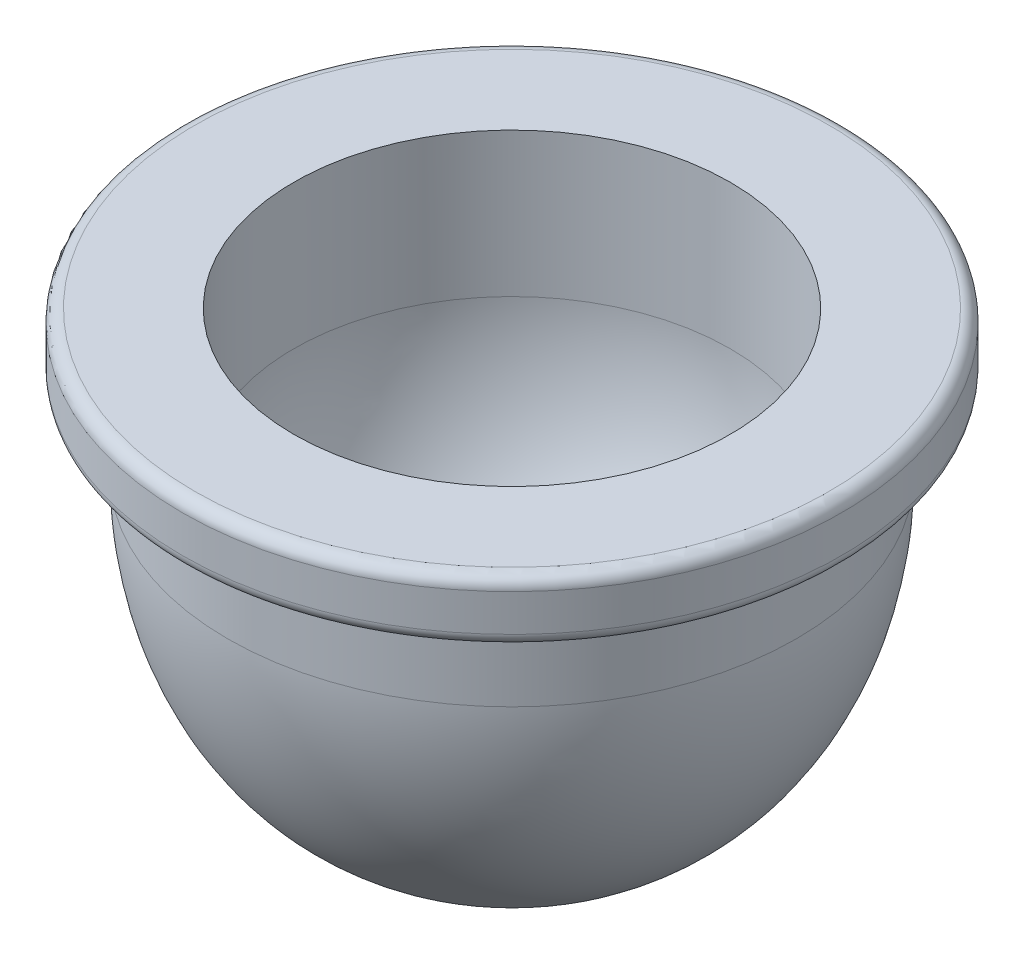
SolidWorks part; units mm, degrees
ref_plane "Front Plane" through (0, 0, 0) normal (0, 0, 1) x (1, 0, 0)
ref_plane "Top Plane" through (0, 0, 0) normal (0, 1, 0) x (1, 0, 0)
ref_plane "Right Plane" through (0, 0, 0) normal (1, 0, 0) x (0, 0, -1)
sketch "Sketch1" plane through (0, 0, 0) normal (0, 0, 1) x (1, 0, 0)
  line L0 (-11.024, 0) -> (0, 0) construction
  line L1 (0, 0) -> (0, 11) construction
  line L2 (0, 11) -> (6.9, 11) construction
  line L3 (6.9, 9.5) -> (6.9, 7.5)
  line L4 (5.3, 11) -> (5.3, 7.5)
  line L5 (0, 1.6) -> (0, 0)
  line L6 (5.3, 11) -> (6.9, 11)
  line L7 (6.9, 11) -> (8, 11)
  line L9 (6.9, 9.5) -> (8, 9.5)
  line L10 (8, 11) -> (8, 9.5)
  line L12 (6.9, 11) -> (6.9, 7.5) construction
  spline S0 degree 3 poles (6.9, 7.5) (6.9, 4.1029) (4.8713, 0) (0, 0) knots 0 0 0 0 1 1 1 1
  spline S1 degree 1 poles (5.3, 7.5) (0, 1.6) knots 0 0 1 1 construction
  spline S2 degree 3 poles (5.3, 7.5) (5.3, 7.1449) (5.2482, 6.4435) (4.9248, 4.9934) (4.2717, 3.6769) (3.3195, 2.6726) (2.4515, 2.0936) (1.5581, 1.769) (0.7242, 1.6261) (0.2358, 1.6) (0, 1.6) knots 0 0 0 0 0.125 0.25 0.5 0.625 0.75 0.875 0.9375 1 1 1 1
  dimension "D2" = 11
revolve "Revolve3" add sketch "Sketch1" angle 360 about L1
fillet "Fillet1" radius 0.3 2 edges at (0, 9.5, -8) (0, 11, -8)
